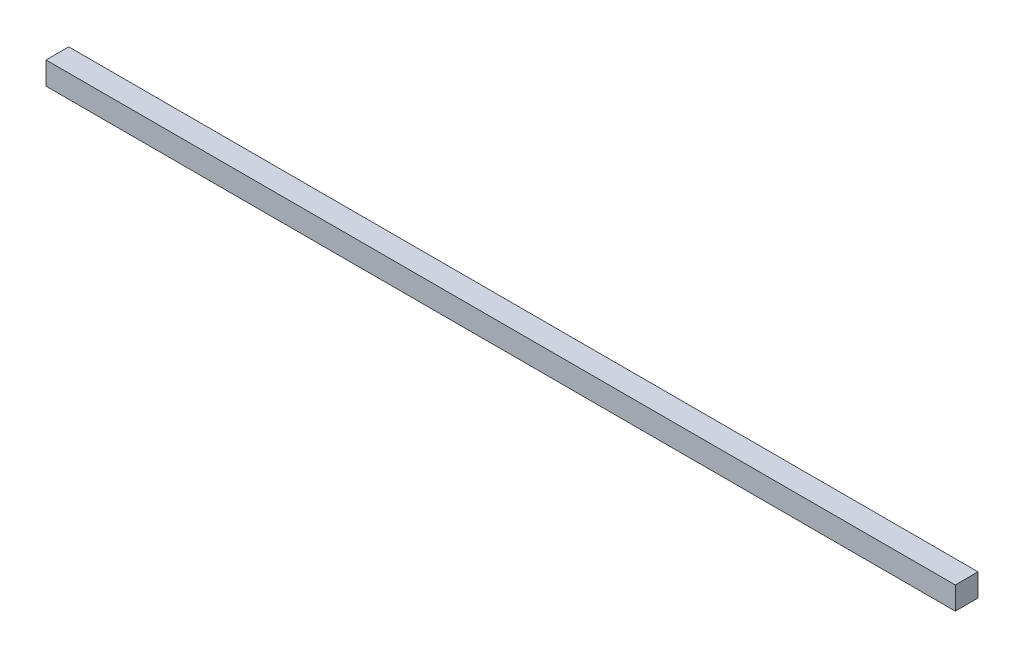
SolidWorks part; units mm, degrees
ref_plane "Front Plane" through (0, 0, 0) normal (0, 0, 1) x (1, 0, 0)
ref_plane "Top Plane" through (0, 0, 0) normal (0, 1, 0) x (1, 0, 0)
ref_plane "Right Plane" through (0, 0, 0) normal (1, 0, 0) x (0, 0, -1)
sketch "Sketch1" plane through (0, 0, 0) normal (1, 0, 0) x (0, 0, -1)
  line L1 (-7.5, 7.5) -> (7.5, 7.5)
  line L2 (-7.5, 7.5) -> (-7.5, -7.5)
  line L3 (-7.5, -7.5) -> (7.5, -7.5)
  line L4 (7.5, 7.5) -> (7.5, -7.5)
  line L5 (-7.5, 7.5) -> (7.5, -7.5) construction
  line L6 (-7.5, -7.5) -> (7.5, 7.5) construction
  point P0 (0, 0)
  dimension "D1" = 15
  dimension "D2" = 15
extrude "Boss-Extrude1" add sketch "Sketch1" along normal blind 600
